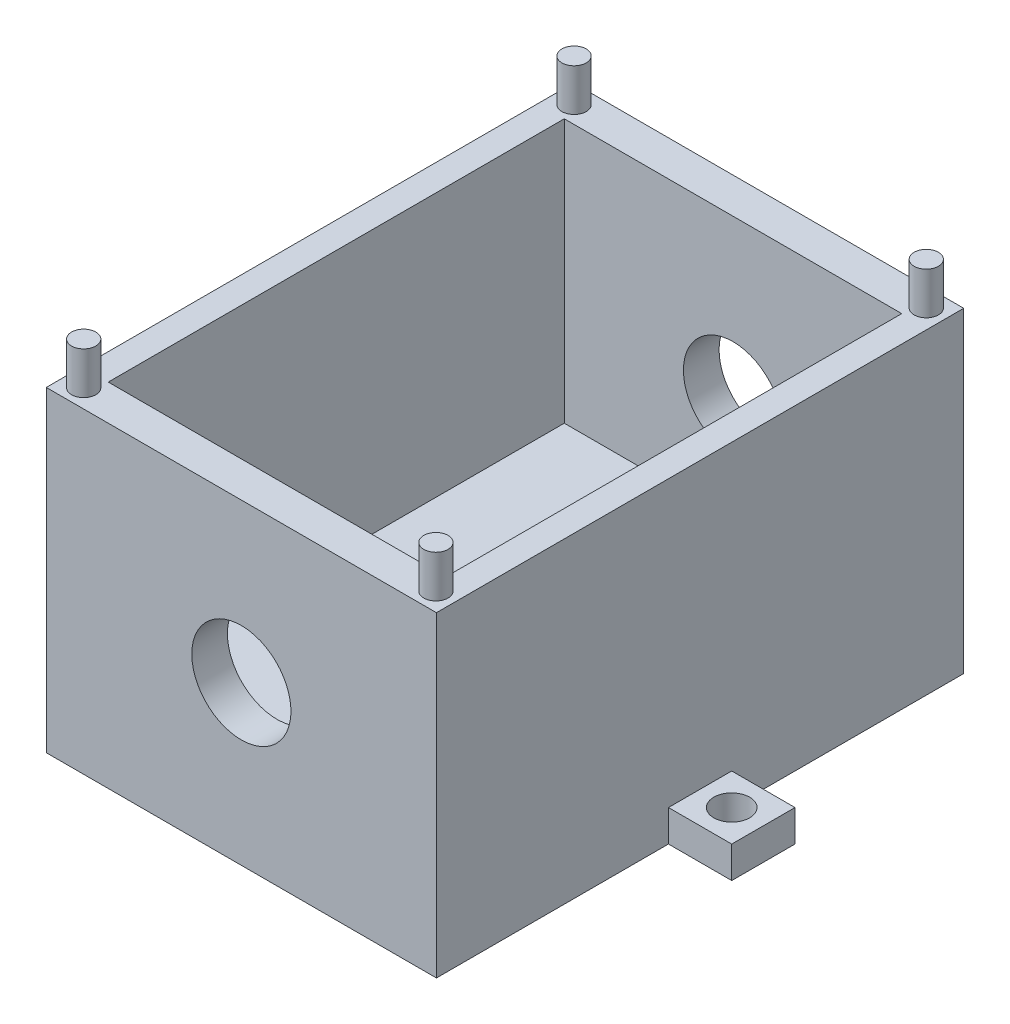
SolidWorks part; units mm, degrees
ref_plane "Front Plane" through (0, 0, 0) normal (0, 0, 1) x (1, 0, 0)
ref_plane "Top Plane" through (0, 0, 0) normal (0, 1, 0) x (1, 0, 0)
ref_plane "Right Plane" through (0, 0, 0) normal (1, 0, 0) x (0, 0, -1)
sketch "Sketch2" plane through (0, 0, 0) normal (0, 1, 0) x (1, 0, 0)
  line L1 (18.5, -25) -> (-18.5, -25)
  line L2 (18.5, -25) -> (18.5, 25)
  line L3 (18.5, 25) -> (-18.5, 25)
  line L4 (-18.5, -25) -> (-18.5, 25)
  line L5 (18.5, -25) -> (-18.5, 25) construction
  line L6 (18.5, 25) -> (-18.5, -25) construction
  line L7 (16, -21.6216) -> (-16, -21.6216)
  line L8 (16, -21.6216) -> (16, 21.6216)
  line L9 (16, 21.6216) -> (-16, 21.6216)
  line L10 (-16, -21.6216) -> (-16, 21.6216)
  line L11 (16, -21.6216) -> (-16, 21.6216) construction
  line L12 (16, 21.6216) -> (-16, -21.6216) construction
  point P0 (0, 0)
  point P6 (0, 0)
  dimension "D1" = 37
  dimension "D2" = 50
  dimension "D3" = 32
extrude "Boss-Extrude1" add sketch "Sketch2" along normal blind 25
sketch "Sketch4" plane through (0, 0, 0) normal (0, -1, 0) x (1, 0, 0)
  line L1 (18.5, -25) -> (-18.5, -25)
  line L2 (18.5, -25) -> (18.5, 25)
  line L3 (18.5, 25) -> (-18.5, 25)
  line L4 (-18.5, -25) -> (-18.5, 25)
  line L5 (18.5, -25) -> (-18.5, 25) construction
  line L6 (18.5, 25) -> (-18.5, -25) construction
  point P0 (0, 0)
extrude "Boss-Extrude2" add sketch "Sketch4" along normal blind 5
sketch "Sketch5" plane through (0, 0, -25) normal (0, 0, -1) x (-1, 0, 0)
  line L0 (0, 25) -> (0, -5) construction
  line L1 (-18.5, 25) -> (18.5, 25) construction
  line L2 (18.5, -5) -> (-18.5, -5) construction
  circle A0 centre (0, 10) radius 4.7
  dimension "D1" = 9.4
extrude "Cut-Extrude1" cut sketch "Sketch5" against normal blind 65
sketch "Sketch6" plane through (0, 25, 0) normal (0, 1, 0) x (1, 0, 0)
  line L0 (0, -16.5) -> (0, 16.5) construction
  line L1 (18.5, 25) -> (-18.5, 25) construction
  line L2 (-16.5, 0) -> (16.5, 0) construction
  circle A0 centre (-16.7, 23.25) radius 1.15
  circle A1 centre (16.7, 23.25) radius 1.15
  circle A2 centre (16.7, -23.25) radius 1.15
  circle A3 centre (-16.7, -23.25) radius 1.15
  dimension "D2" = 2.3
  dimension "D1" = 16.7
  dimension "D3" = 1.75
extrude "Boss-Extrude3" add sketch "Sketch6" along normal blind 4
sketch "Sketch7" plane through (0, -5, 0) normal (0, -1, 0) x (1, 0, 0)
  line L0 (0, 0) -> (-18.5, 0) construction
  line L1 (-18.5, 25) -> (-18.5, -25) construction
  line L4 (-18.5, 0) -> (-18.5, 3)
  line L5 (-18.5, 0) -> (-18.5, -3)
  line L6 (-18.5, -3) -> (-24.5, -3)
  line L7 (-24.5, -3) -> (-24.5, 3)
  line L8 (-24.5, 3) -> (-18.5, 3)
  line L14 (-24.5, 0) -> (-18.5, 0) construction
  circle A0 centre (-21.5, 0) radius 1.7
  dimension "D7" = 3.4
  dimension "D1" = 3
  dimension "D2" = 3
  dimension "D3" = 6
  dimension "D4" = 21.5
extrude "Boss-Extrude4" add sketch "Sketch7" against normal blind 3
mirror "Mirror1" about plane through (0, 0, 0) normal (1, 0, 0) of "Boss-Extrude4"
